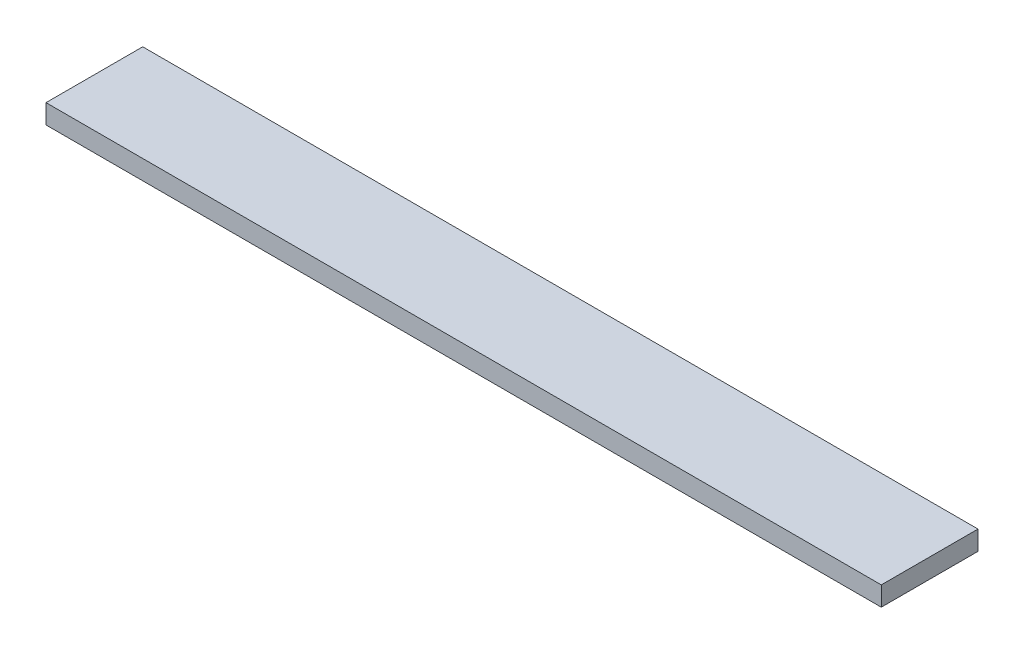
SolidWorks part; units mm, degrees
ref_plane "Front Plane" through (0, 0, 0) normal (0, 0, 1) x (1, 0, 0)
ref_plane "Top Plane" through (0, 0, 0) normal (0, 1, 0) x (1, 0, 0)
ref_plane "Right Plane" through (0, 0, 0) normal (1, 0, 0) x (0, 0, -1)
sketch "Sketch1" plane through (0, 0, 0) normal (0, 0, 1) x (1, 0, 0)
  line L1 (0, 0) -> (-215.9, 0)
  line L2 (0, 0) -> (0, -5)
  line L3 (0, -5) -> (-215.9, -5)
  line L4 (-215.9, 0) -> (-215.9, -5)
  dimension "D1" = 5
  dimension "D2" = 215.9
extrude "Boss-Extrude1" add sketch "Sketch1" along normal blind 25
